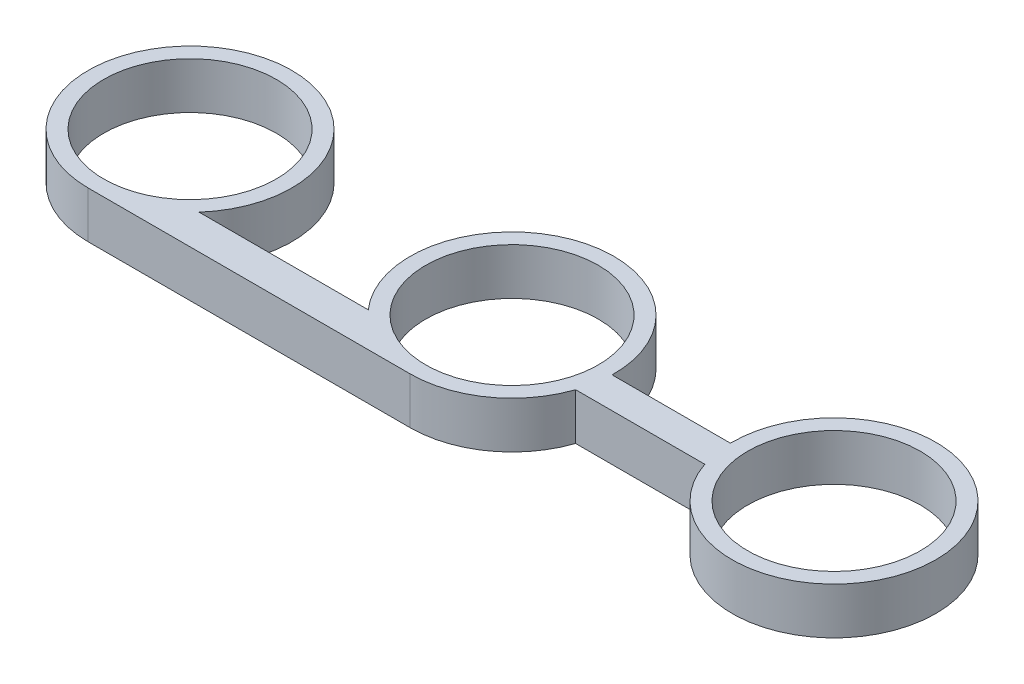
SolidWorks part; units mm, degrees
ref_plane "Front Plane" through (0, 0, 0) normal (0, 0, 1) x (1, 0, 0)
ref_plane "Top Plane" through (0, 0, 0) normal (0, 1, 0) x (1, 0, 0)
ref_plane "Right Plane" through (0, 0, 0) normal (1, 0, 0) x (0, 0, -1)
sketch "Sketch1" plane through (0, 0, 0) normal (0, 1, 0) x (1, 0, 0)
  line L0 (-18.65, 0) -> (18.65, 0) construction
  line L1 (-18.65, -5.9) -> (0, -5.9)
  line L2 (-14.2228, -3.9) -> (-4.4272, -3.9)
  line L3 (0, -5.9) -> (18.65, -5.9) construction
  line L4 (5.5857, -1.9) -> (13.0643, -1.9)
  line L5 (5.8992, -0.1) -> (12.7508, -0.1)
  circle A0 centre (0, 0) radius 5
  arc A1 (0, -5.9) -> (5.5857, -1.9) centre (0, 0) ccw
  circle A2 centre (18.65, 0) radius 5
  circle A3 centre (-18.65, 0) radius 5
  arc A4 (-14.2228, -3.9) -> (-18.65, -5.9) centre (-18.65, 0) ccw
  arc A5 (13.0643, -1.9) -> (12.7508, -0.1) centre (18.65, 0) ccw
  arc A6 (5.8992, -0.1) -> (-4.4272, -3.9) centre (0, 0) ccw
  point P3 (5.5857, -1.9)
  point P7 (0, 0)
  point P13 (-14.2228, -3.9)
  point P14 (-4.4272, -3.9)
  point P17 (13.0643, -1.9)
  point P20 (5.8992, -0.1)
  point P21 (12.7508, -0.1)
  dimension "D1" = 10
  dimension "D2" = 11.8
  dimension "D3" = 18.65
  dimension "D4" = 2
  dimension "D5" = 8
  dimension "D7" = 1.8
extrude "Boss-Extrude2" add sketch "Sketch1" along normal blind 2.7
